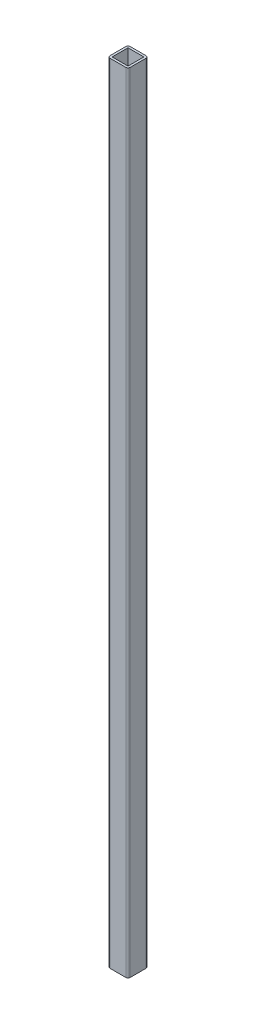
SolidWorks part; units mm, degrees
material "Plain Carbon Steel"
ref_plane "Front Plane" through (0, 0, 0) normal (0, 0, 1) x (1, 0, 0)
ref_plane "Top Plane" through (0, 0, 0) normal (0, 1, 0) x (1, 0, 0)
ref_plane "Right Plane" through (0, 0, 0) normal (1, 0, 0) x (0, 0, -1)
sketch "Sketch1" plane through (0, 0, 0) normal (0, 1, 0) x (1, 0, 0)
  line L1 (2.8, 0) -> (22.8, 0)
  line L2 (0, -2.8) -> (0, -22.8)
  line L3 (2.8, -25.6) -> (22.8, -25.6)
  line L4 (25.6, -2.8) -> (25.6, -22.8)
  arc A0 (22.8, 0) -> (25.6, -2.8) centre (22.8, -2.8) cw
  arc A1 (22.8, -25.6) -> (25.6, -22.8) centre (22.8, -22.8) ccw
  arc A2 (0, -22.8) -> (2.8, -25.6) centre (2.8, -22.8) ccw
  arc A3 (2.8, 0) -> (0, -2.8) centre (2.8, -2.8) ccw
  point P7 (25.6, 0)
  point P10 (25.6, -25.6)
  point P15 (0, 0)
  dimension "D2" = 2.8
  dimension "D1" = 25.6
extrude "Boss-Extrude1" add sketch "Sketch1" along normal blind 996.1
sketch "Sketch3" plane through (0, 0, 0) normal (0, -1, 0) x (-1, 0, 0)
  line L4 (-2.8, -2.8) -> (-22.8, -2.8)
  line L5 (-2.8, -2.8) -> (-2.8, -22.8)
  line L6 (-2.8, -22.8) -> (-22.8, -22.8)
  line L7 (-22.8, -2.8) -> (-22.8, -22.8)
  line L8 (-2.8, -2.8) -> (-22.8, -22.8) construction
  line L9 (-2.8, -22.8) -> (-22.8, -2.8) construction
  point P6 (-12.8, -12.8)
extrude "Cut-Extrude1" cut sketch "Sketch3" against normal blind 1040.5
